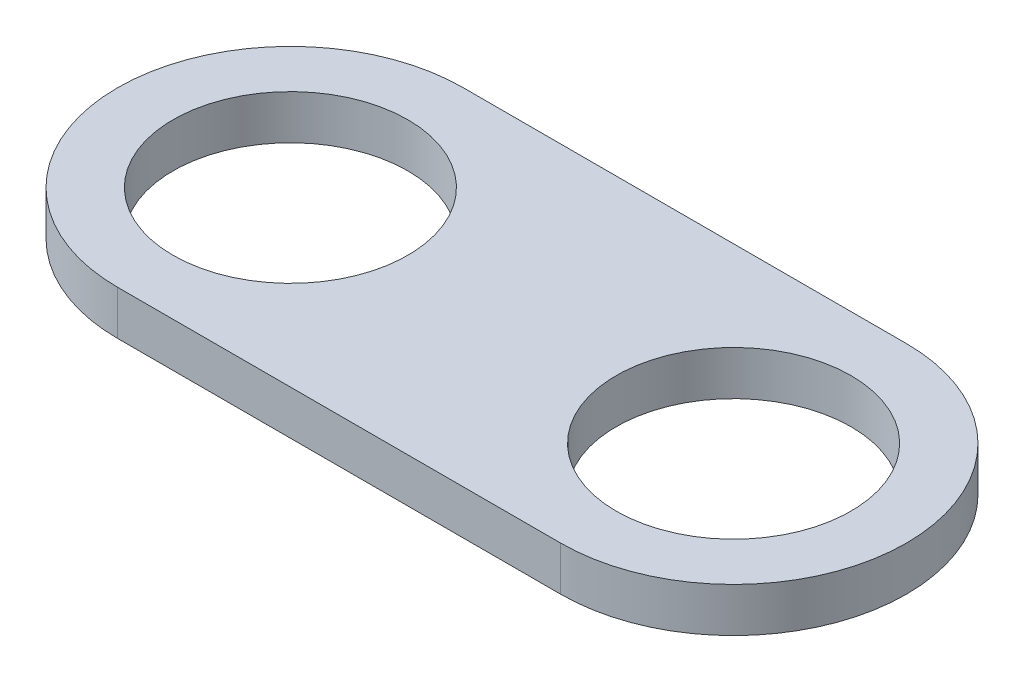
SolidWorks part; units mm, degrees
ref_plane "Front Plane" through (0, 0, 0) normal (0, 0, 1) x (1, 0, 0)
ref_plane "Top Plane" through (0, 0, 0) normal (0, 1, 0) x (1, 0, 0)
ref_plane "Right Plane" through (0, 0, 0) normal (1, 0, 0) x (0, 0, -1)
sketch "Sketch1" plane through (0, 0, 0) normal (0, 1, 0) x (1, 0, 0)
  line L0 (-10, 0) -> (10, 0) construction
  line L1 (-10, 7.8) -> (10, 7.8)
  line L2 (-10, -7.8) -> (10, -7.8)
  circle A0 centre (-10, 0) radius 5.3
  circle A1 centre (10, 0) radius 5.3
  arc A2 (-10, 7.8) -> (-10, -7.8) centre (-10, 0) ccw
  arc A3 (10, -7.8) -> (10, 7.8) centre (10, 0) ccw
  circle A4 centre (-10, 0) radius 7.8 construction
  circle A5 centre (10, 0) radius 7.8 construction
  point P4 (0, 0)
  dimension "D1" = 2.5
  dimension "D2" = 20
extrude "Boss-Extrude1" add sketch "Sketch1" along normal blind 2
